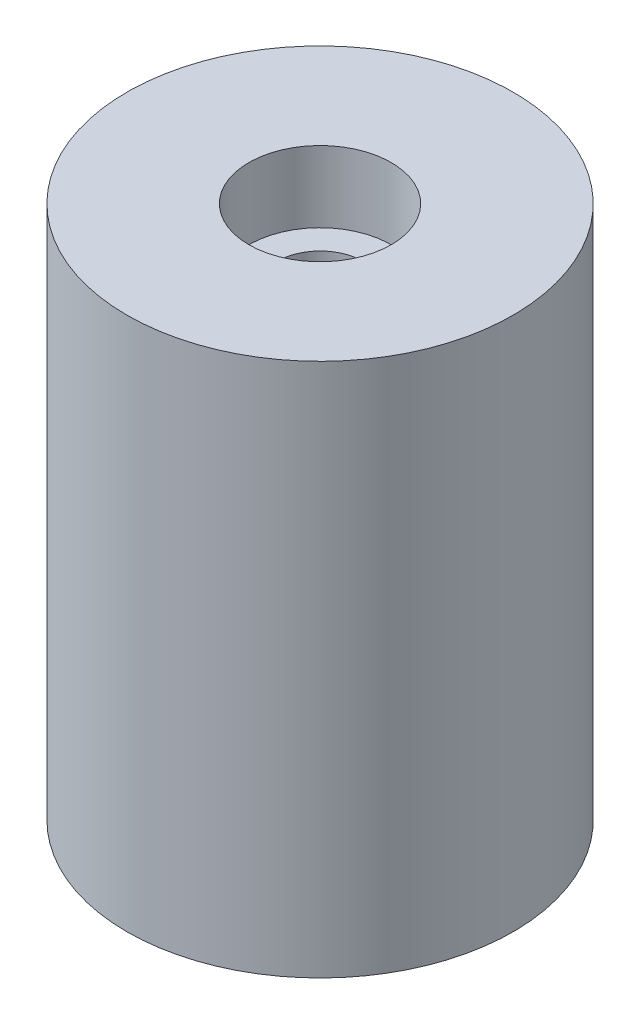
SolidWorks part; units mm, degrees
material "ABS"
ref_plane "Front Plane" through (0, 0, 0) normal (0, 0, 1) x (1, 0, 0)
ref_plane "Top Plane" through (0, 0, 0) normal (0, 1, 0) x (1, 0, 0)
ref_plane "Right Plane" through (0, 0, 0) normal (1, 0, 0) x (0, 0, -1)
sketch "Sketch1" plane through (0, 0, 0) normal (0, 1, 0) x (1, 0, 0)
  circle A0 centre (0, 0) radius 10.85
  dimension "D1" = 21.7
extrude "Boss-Extrude1" add sketch "Sketch1" along normal blind 30
sketch "Sketch2" plane through (0, 30, 0) normal (0, 1, 0) x (1, 0, 0)
  point P0 (0, 0)
hole_wizard "CBORE for M4 SHCS1" positions "Sketch2" profile "Sketch3" counterbore size "M4" standard "ANSI Metric" end condition through all
sketch "Sketch3" plane through (0, 30, 0) normal (1, 0, 0) x (0, 0, 1)
  line L0 (0, 0) -> (0, 30)
  line L1 (0, 30) -> (2.4, 30)
  line L3 (2.4, 30) -> (2.4, 4)
  line L4 (2.4, 4) -> (4, 4)
  line L5 (4, 4) -> (4, 0)
  line L7 (4, 0) -> (0, 0)
  line L11 (0, -6.35) -> (0, 107.95) construction
  dimension "Thru Hole Dia." = 4.8
  dimension "Thru Hole Depth" = 30
  dimension "C'Bore Dia." = 8
  dimension "C'Bore Depth" = 4
